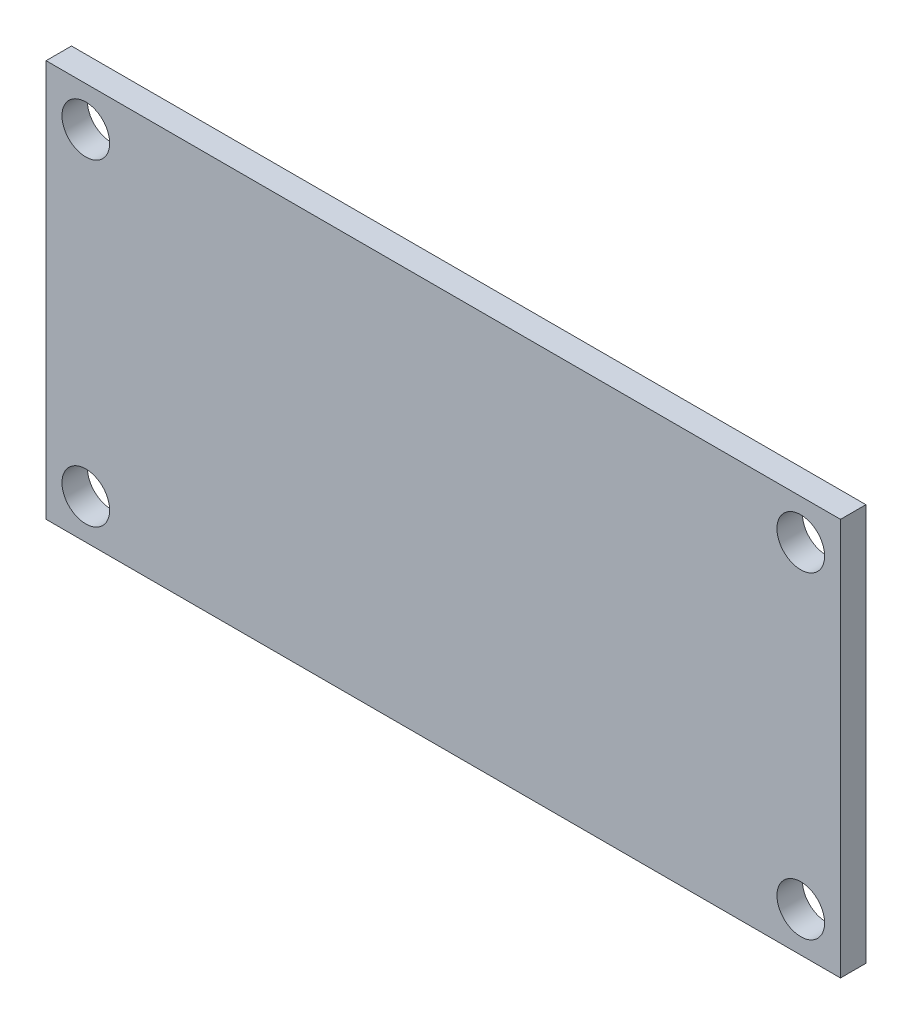
SolidWorks part; units mm, degrees
ref_plane "Front Plane" through (0, 0, 0) normal (0, 0, 1) x (1, 0, 0)
ref_plane "Top Plane" through (0, 0, 0) normal (0, 1, 0) x (1, 0, 0)
ref_plane "Right Plane" through (0, 0, 0) normal (1, 0, 0) x (0, 0, -1)
sketch "Sketch1" plane through (0, 0, 0) normal (0, 0, 1) x (1, 0, 0)
  line L1 (0, 0) -> (50, 0)
  line L2 (0, 0) -> (0, 25)
  line L3 (0, 25) -> (50, 25)
  line L4 (50, 0) -> (50, 25)
  dimension "D1" = 25
  dimension "D2" = 50
extrude "Boss-Extrude1" add sketch "Sketch1" along normal blind 1.6
sketch "Sketch2" plane through (0, 0, 0) normal (0, 0, -1) x (-1, 0, 0)
  line L0 (0, 25) -> (0, 0) construction
  line L1 (0, 0) -> (-50, 0) construction
  line L2 (-50, 0) -> (-50, 25) construction
  line L3 (-50, 25) -> (0, 25) construction
  circle A0 centre (-2.5, 2.5) radius 1.5
  circle A1 centre (-47.5, 2.5) radius 1.5
  circle A2 centre (-47.5, 22.5) radius 1.5
  circle A3 centre (-2.5, 22.5) radius 1.5
  dimension "D9" = 3
  dimension "D10" = 3
  dimension "D11" = 3
  dimension "D12" = 3
  dimension "D1" = 2.5
  dimension "D2" = 2.5
  dimension "D3" = 2.5
  dimension "D4" = 2.5
  dimension "D5" = 2.5
  dimension "D6" = 2.5
  dimension "D7" = 2.5
  dimension "D8" = 2.5
extrude "Cut-Extrude1" cut sketch "Sketch2" against normal blind 1.6
